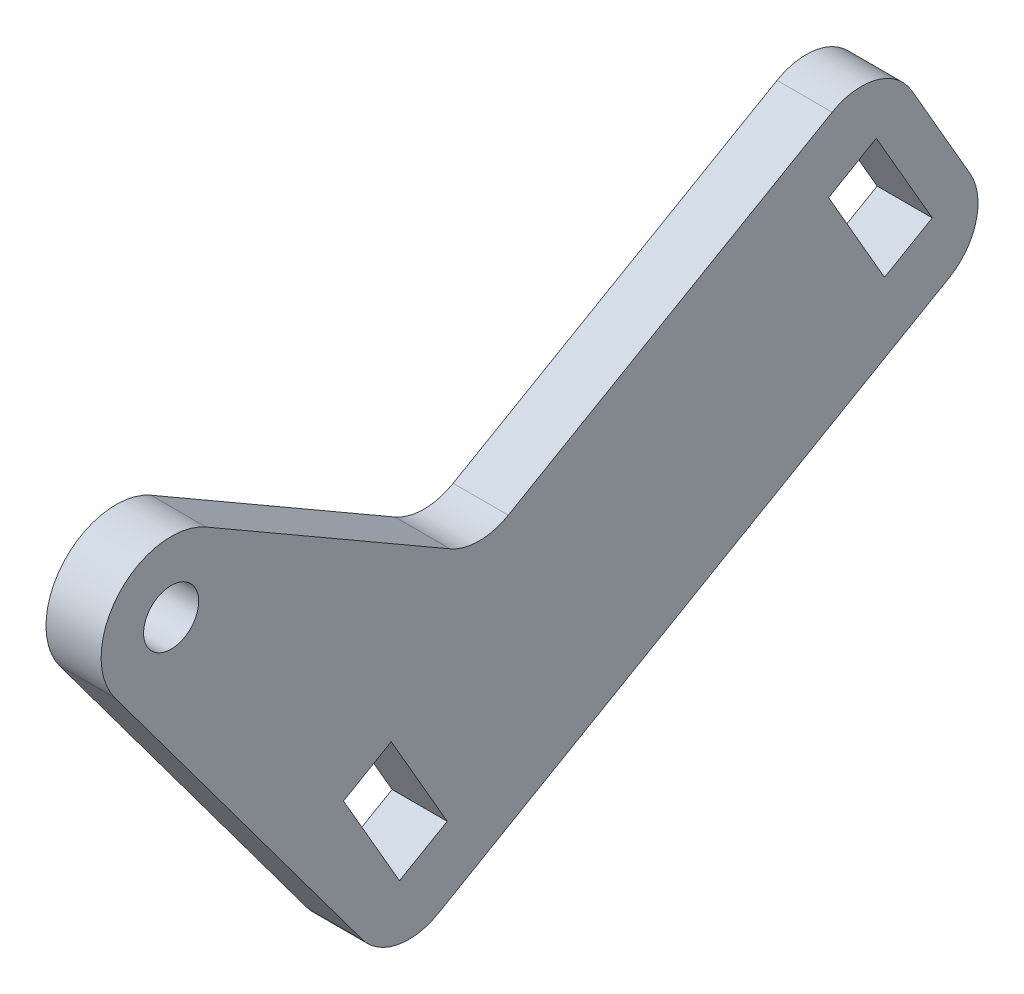
SolidWorks part; units mm, degrees
ref_plane "Front Plane" through (0, 0, 0) normal (0, 0, 1) x (1, 0, 0)
ref_plane "Top Plane" through (0, 0, 0) normal (0, 1, 0) x (1, 0, 0)
ref_plane "Right Plane" through (0, 0, 0) normal (1, 0, 0) x (0, 0, -1)
sketch "Sketch1" plane through (0, 0, 0) normal (1, 0, 0) x (0, 0, -1)
  line L0 (-13.3228, -15.0243) -> (-19.6728, -4.0257)
  line L1 (-13.3228, -15.0243) -> (19.6728, 4.0257)
  line L2 (-19.6728, -4.0257) -> (13.3228, 15.0243)
  line L3 (19.6728, 4.0257) -> (13.3228, 15.0243)
  line L4 (-13.3228, -15.0243) -> (13.3228, 15.0243) construction
  line L5 (-19.6728, -4.0257) -> (19.6728, 4.0257) construction
  line L6 (0, 0) -> (-25.414, 0) construction
  line L7 (-13.1982, -7.62) -> (13.1982, 7.62) construction
  line L9 (48.8706, -8.4463) -> (-17.1206, -46.5463) construction
  line L12 (15.875, -27.4963) -> (0, 0) construction
  line L13 (13.3228, 15.0243) -> (48.8706, -8.4463) construction
  line L14 (-19.6728, -4.0257) -> (-17.1206, -46.5463) construction
  line L15 (46.1209, -10.0338) -> (42.9459, -4.5345) construction
  line L16 (-41.8965, 50.8) -> (41.8965, 50.8) construction
  line L17 (0, 50.8) -> (0, 0) construction
  line L18 (13.3228, 15.0243) -> (-21.356, 15.0243) construction
  point P1 (0, 0)
  line B0 (-12.9098, -11.1196) -> (-10.3117, -9.6196)
  line B1 (-12.9098, -11.1196) -> (-16.0848, -5.6204)
  line B2 (-16.0848, -5.6204) -> (-13.4867, -4.1204)
  line B3 (-10.3117, -9.6196) -> (-13.4867, -4.1204)
  line B4 (-12.9098, -11.1196) -> (-13.4867, -4.1204) construction
  line B5 (-16.0848, -5.6204) -> (-10.3117, -9.6196) construction
  line B6 (13.4867, 4.1204) -> (16.0848, 5.6204)
  line B7 (13.4867, 4.1204) -> (10.3117, 9.6196)
  line B8 (10.3117, 9.6196) -> (12.9098, 11.1196)
  line B9 (16.0848, 5.6204) -> (12.9098, 11.1196)
  line B10 (13.4867, 4.1204) -> (12.9098, 11.1196) construction
  line B11 (10.3117, 9.6196) -> (16.0848, 5.6204) construction
  dimension "D1" = 12.7
  dimension "D2" = 38.1
  dimension "D3" = 30
  dimension "D4" = 3.81
  dimension "D5" = 76.2
  dimension "D6" = 6.35
  dimension "D7" = 3.175
  dimension "D8" = 50.8
sketch_block_instance "Block1-1"
sketch_block "Block1" parameters "D1"=3, "D2"=6.35
sketch_block_instance "Block1-2"
sketch "Sketch2" plane through (0, 0, 0) normal (1, 0, 0) x (0, 0, -1)
  line L6 (-16.0213, -5.7304) -> (-12.9733, -11.0096)
  line L7 (-16.0213, -5.7304) -> (-13.4232, -4.2304)
  line L8 (-12.9733, -11.0096) -> (-10.3752, -9.5096)
  line L9 (-13.4232, -4.2304) -> (-10.3752, -9.5096)
  line L10 (-16.0213, -5.7304) -> (-10.3752, -9.5096) construction
  line L11 (-12.9733, -11.0096) -> (-13.4232, -4.2304) construction
  line L12 (10.3752, 9.5096) -> (13.4232, 4.2304)
  line L13 (10.3752, 9.5096) -> (12.9733, 11.0096)
  line L14 (13.4232, 4.2304) -> (16.0213, 5.7304)
  line L15 (12.9733, 11.0096) -> (16.0213, 5.7304)
  line L16 (10.3752, 9.5096) -> (16.0213, 5.7304) construction
  line L17 (13.4232, 4.2304) -> (12.9733, 11.0096) construction
  line L19 (-19.6728, -4.0257) -> (13.3228, 15.0243)
  line L20 (13.3228, 15.0243) -> (19.6728, 4.0257)
  line L21 (-3.175, 5.4993) -> (0, 0) construction
  line L22 (-13.1982, -7.62) -> (13.1982, 7.62) construction
  line L24 (19.6728, 4.0257) -> (-13.3228, -15.0243)
  line L27 (-10.3117, -9.6196) -> (-13.4867, -4.1204) construction
  line L28 (-13.3228, -15.0243) -> (-19.6728, -4.0257)
  line L29 (15.875, -27.4963) -> (0, 0) construction
  line L30 (-13.1982, -7.62) -> (-16.4978, -9.525) construction
  point P11 (-13.1982, -7.62)
  point P12 (13.1982, 7.62)
  dimension "D1" = 3
  dimension "D2" = 6.096
  dimension "D3" = 12.7
  dimension "D4" = 38.1
extrude "Boss-Extrude1" add sketch "Sketch2" along normal mid plane 3
sketch "Sketch3" plane through (0, 0, 0) normal (1, 0, 0) x (0, 0, -1)
  line L0 (-25.4, 7.62) -> (71.9673, -21.4001) construction
  line L1 (-25.4, 7.62) -> (75.1092, 22.468) construction
  circle A0 centre (-25.4, 7.62) radius 1.5
  arc A1 (71.9673, -21.4001) -> (75.1092, 22.468) centre (-25.4, 7.62) ccw construction
  arc A2 (73.4048, -21.8286) -> (76.5931, 22.6873) centre (-25.4, 7.62) ccw
  arc A3 (70.5298, -20.9717) -> (73.6253, 22.2488) centre (-25.4, 7.62) ccw
  arc A4 (70.5298, -20.9717) -> (73.4048, -21.8286) centre (71.9673, -21.4001) ccw
  arc A5 (76.5931, 22.6873) -> (73.6253, 22.2488) centre (75.1092, 22.468) ccw
  circle A6 centre (-25.4, 7.62) radius 3.81
  arc A7 (71.9673, -21.4001) -> (75.1092, 22.468) centre (-25.4, 7.62) ccw construction
  arc A8 (75.6186, -22.4884) -> (78.8783, 23.0248) centre (-25.4, 7.62) ccw
  arc A9 (68.316, -20.3119) -> (71.3401, 21.9112) centre (-25.4, 7.62) ccw
  arc A10 (68.316, -20.3119) -> (75.6186, -22.4884) centre (71.9673, -21.4001) ccw
  arc A11 (78.8783, 23.0248) -> (71.3401, 21.9112) centre (75.1092, 22.468) ccw
  point P4 (75.9404, 0.3619)
  point P14 (75.9404, 0.3619)
  dimension "D1" = 3
  dimension "D2" = 3
  dimension "D3" = 7.62
  dimension "D4" = 7.62
  dimension "D5" = 25
  dimension "D6" = 101.6
  dimension "D7" = 25.4
  dimension "D8" = 7.62
extrude "Boss-Extrude2" add sketch "Sketch3" along normal mid plane 3 separate body contours A6 A0 | A9 A11 A8 A10
sketch "Sketch4" plane through (1.5, 0, 0) normal (1, 0, 0) x (0, 0, -1)
  line L0 (-13.3228, -15.0243) -> (-28.4583, 5.3478)
  line L1 (-23.495, 10.9196) -> (-8.6409, 2.3435)
  line L3 (-13.3228, -15.0243) -> (-19.6728, -4.0257)
  line L4 (-19.6728, -4.0257) -> (13.3228, 15.0243)
  line L5 (13.3228, 15.0243) -> (19.6728, 4.0257)
  circle A4 centre (-25.4, 7.62) radius 3.81 construction
  circle A5 centre (-25.4, 7.62) radius 3.81
  dimension "D1" = 60
extrude "Boss-Extrude3" add sketch "Sketch4" against normal up to surface (3 mm away) up to face at (-1.5, 0, 0)
fillet "Fillet1" radius 3.175 4 edges at (0, 4.0257, -19.6728) (0, -15.0243, 13.3228) (0, 2.3435, 8.6409) (0, 15.0243, -13.3228)
equation "\"PlateThickness\"=0.11811"
equation "\"D1@Boss-Extrude2\"=\"PlateThickness\""
equation "\"D1@Boss-Extrude1\"=\"PlateThickness\""
